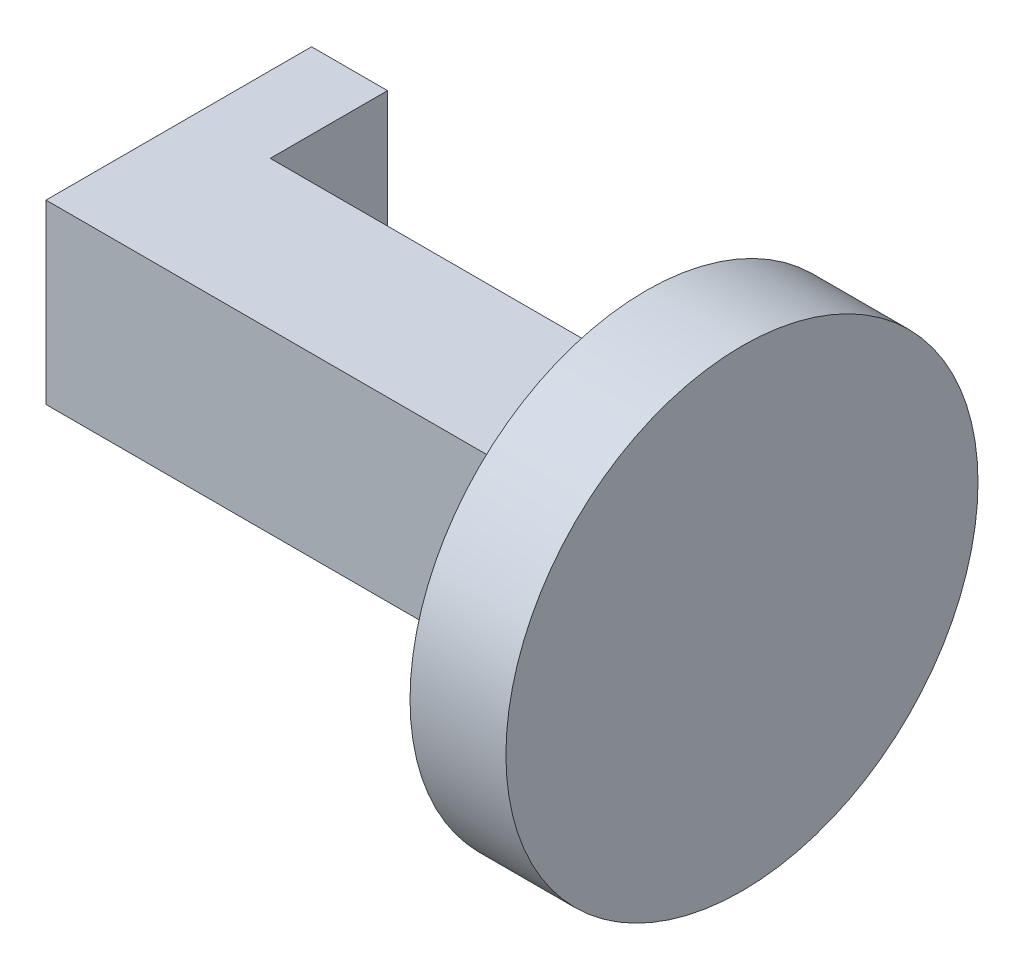
SolidWorks part; units mm, degrees
ref_plane "前视基准面" through (0, 0, 0) normal (0, 0, 1) x (1, 0, 0)
ref_plane "上视基准面" through (0, 0, 0) normal (0, 1, 0) x (1, 0, 0)
ref_plane "右视基准面" through (0, 0, 0) normal (1, 0, 0) x (0, 0, -1)
other "Configuration Table"
sketch "草图1" plane through (0, 0, 0) normal (0, 1, 0) x (1, 0, 0)
  line L0 (-15.275, 0) -> (-10.125, 0)
  line L1 (-15.275, -5.025) -> (15.275, -5.025)
  line L3 (-10.125, 5.025) -> (15.275, 5.025)
  line L4 (15.275, -5.025) -> (15.275, 5.025)
  line L5 (-15.275, -5.025) -> (15.275, 5.025) construction
  line L6 (-10.125, 3.3308) -> (15.275, -5.025) construction
  line L7 (-10.125, 5.025) -> (-10.125, -5.025)
  line L8 (-15.275, -5.025) -> (-15.275, 12.975)
  line L9 (-15.275, 12.975) -> (-10.125, 12.975)
  line L10 (-10.125, 12.975) -> (-10.125, 5.025)
  point P0 (0, 0)
extrude "凸台-拉伸1" add sketch "草图1" along normal blind 12 contours L3 L7 L1 L4 | L10 L9 L8 L0 L7 | L8 L1 L7 L0
sketch "草图2" plane through (15.275, 0, 0) normal (1, 0, 0) x (0, 0, -1)
  line L0 (-5.025, 12) -> (0, 6) construction
  line L1 (-5.025, 12) -> (5.025, 12)
  line L2 (-5.025, 12) -> (-5.025, 0)
  line L3 (-5.025, 0) -> (5.025, 0)
  line L4 (5.025, 12) -> (5.025, 0)
  line L5 (5.025, 12) -> (0, 6) construction
  circle A0 centre (0, 6) radius 0.6
extrude "凸台-拉伸2" add sketch "草图2" along normal blind 11.6 contours A0
sketch "草图3" plane through (26.875, 0, 0) normal (1, 0, 0) x (0, 0, -1)
  circle A0 centre (0, 6) radius 16
extrude "凸台-拉伸3" add sketch "草图3" against normal blind 6.5
